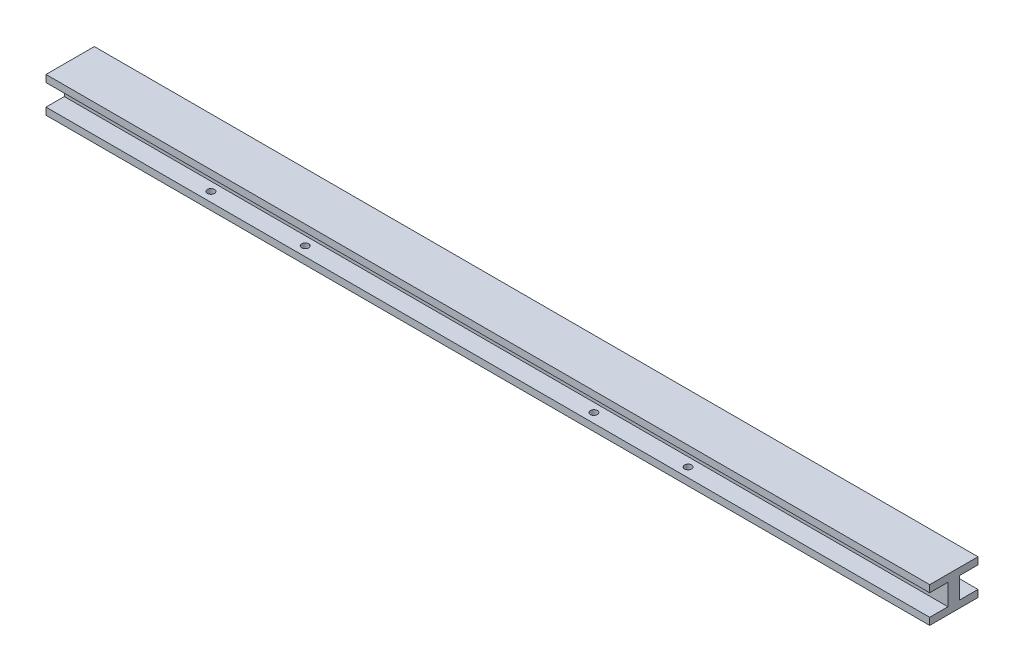
SolidWorks part; units mm, degrees
ref_plane "Front Plane" through (0, 0, 0) normal (0, 0, 1) x (1, 0, 0)
ref_plane "Top Plane" through (0, 0, 0) normal (0, 1, 0) x (1, 0, 0)
ref_plane "Right Plane" through (0, 0, 0) normal (1, 0, 0) x (0, 0, -1)
sketch "Sketch1" plane through (0, 0, 0) normal (1, 0, 0) x (0, 0, -1)
  line L0 (51, -12) -> (82, -12)
  line L1 (0, 0) -> (82, 0)
  line L2 (0, 0) -> (0, -12)
  line L3 (0, -12) -> (31, -12)
  line L4 (82, 0) -> (82, -12)
  line L6 (51, -12) -> (51, -48)
  line L8 (31, -12) -> (31, -48)
  line L9 (31, -48) -> (0, -48)
  line L10 (82, -48) -> (51, -48)
  line L11 (82, -48) -> (82, -60)
  line L12 (82, -60) -> (0, -60)
  line L13 (0, -48) -> (0, -60)
  dimension "D1" = 12
  dimension "D2" = 82
  dimension "D3" = 20
  dimension "D4" = 31
  dimension "D5" = 60
extrude "Boss-Extrude1" add sketch "Sketch1" along normal blind 1500 contours L3 L8 L9 L13 L12 L11 L10 L6 L0 L4 L1 L2
sketch "Sketch4" plane through (0, -60, 0) normal (0, -1, 0) x (-1, 0, 0)
  line L0 (0, 82) -> (0, 0) construction
  line L1 (-1500, 0) -> (0, 0) construction
  line L2 (-1500, 82) -> (0, 82) construction
  circle A0 centre (-424, 16) radius 6
  circle A1 centre (-424, 66) radius 6
  circle A2 centre (-264, 66) radius 6
  circle A3 centre (-264, 16) radius 6
  circle A4 centre (-1074, 66) radius 6
  circle A5 centre (-914, 66) radius 6
  circle A6 centre (-1074, 16) radius 6
  circle A7 centre (-914, 16) radius 6
  dimension "D2" = 12
  dimension "D4" = 12
  dimension "D7" = 12
  dimension "D11" = 12
  dimension "D13" = 12
  dimension "D19" = 12
  dimension "D21" = 12
  dimension "D22" = 12
  dimension "D1" = 424
  dimension "D3" = 16
  dimension "D5" = 424
  dimension "D6" = 16
  dimension "D8" = 160
  dimension "D9" = 16
  dimension "D10" = 16
  dimension "D12" = 160
  dimension "D14" = 16
  dimension "D15" = 650
  dimension "D16" = 650
  dimension "D17" = 160
  dimension "D18" = 160
  dimension "D20" = 16
  dimension "D23" = 16
  dimension "D24" = 16
extrude "Cut-Extrude1" cut sketch "Sketch4" against normal up to next and the other way through all
equation "\"D4@Sketch4\"=\"D2@Sketch4\""
equation "\"D5@Sketch4\"=\"D1@Sketch4\""
equation "\"D6@Sketch4\"=\"D3@Sketch4\""
equation "\"D7@Sketch4\"=\"D2@Sketch4\""
equation "\"D9@Sketch4\"=\"D6@Sketch4\""
equation "\"D10@Sketch4\"=\"D9@Sketch4\""
equation "\"D11@Sketch4\"=\"D7@Sketch4\""
equation "\"D12@Sketch4\"=\"D8@Sketch4\""
equation "\"D13@Sketch4\"=\"D2@Sketch4\""
equation "\"D14@Sketch4\"=\"D6@Sketch4\""
equation "\"D16@Sketch4\"=\"D15@Sketch4\""
equation "\"D17@Sketch4\"=\"D8@Sketch4\""
equation "\"D18@Sketch4\"=\"D17@Sketch4\""
equation "\"D19@Sketch4\"=\"D13@Sketch4\""
equation "\"D20@Sketch4\"=\"D14@Sketch4\""
equation "\"D21@Sketch4\"=\"D19@Sketch4\""
equation "\"D22@Sketch4\"=\"D21@Sketch4\""
equation "\"D23@Sketch4\"=\"D14@Sketch4\""
equation "\"D24@Sketch4\"=\"D20@Sketch4\""
